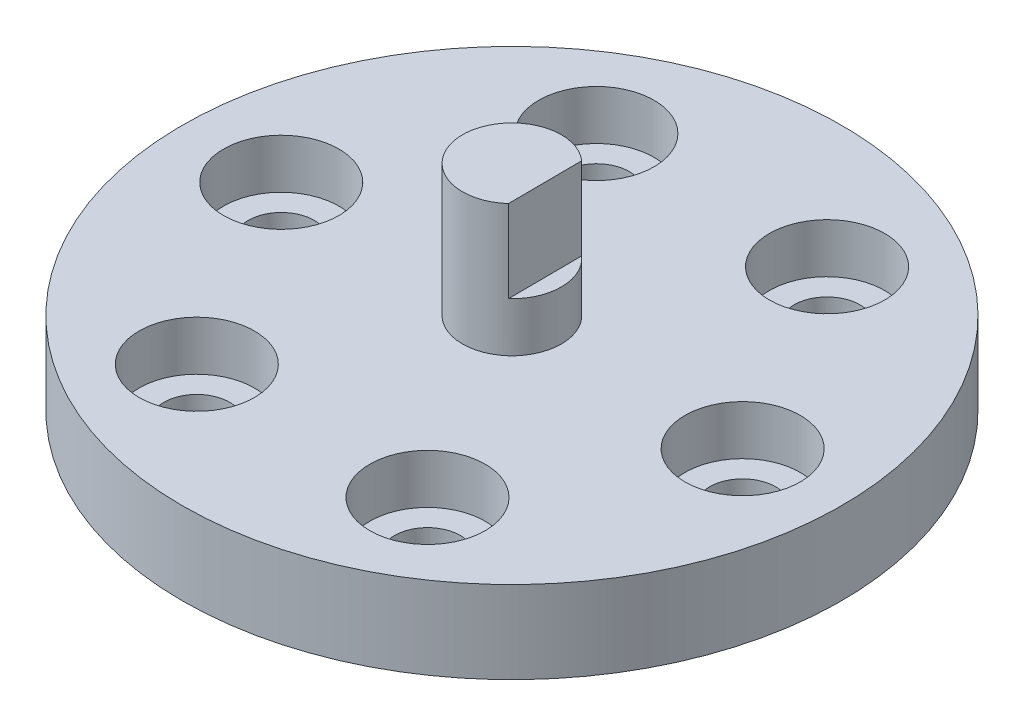
SolidWorks part; units mm, degrees
ref_plane "前视基准面" through (0, 0, 0) normal (0, 0, 1) x (1, 0, 0)
ref_plane "上视基准面" through (0, 0, 0) normal (0, 1, 0) x (1, 0, 0)
ref_plane "右视基准面" through (0, 0, 0) normal (1, 0, 0) x (0, 0, -1)
other "Configuration Table"
sketch "草图1" plane through (0, 0, 0) normal (0, 1, 0) x (1, 0, 0)
  circle A0 centre (0, 0) radius 20
  dimension "D1" = 40
extrude "凸台-拉伸1" add sketch "草图1" along normal blind 5
sketch "草图2" plane through (0, 5, 0) normal (0, 1, 0) x (1, 0, 0)
  circle A0 centre (14, 0) radius 2
  circle A1 centre (7, -12.1244) radius 2
  circle A2 centre (-7, -12.1244) radius 2
  circle A3 centre (-14, 0) radius 2
  circle A4 centre (-7, 12.1244) radius 2
  circle A5 centre (7, 12.1244) radius 2
  point P16 (0, 0)
  dimension "D1" = 4
  dimension "D2" = 14
  dimension "D3" = 6
extrude "切除-拉伸1" cut sketch "草图2" against normal through all
sketch "草图3" plane through (0, 5, 0) normal (0, 1, 0) x (1, 0, 0)
  circle A0 centre (14, 0) radius 3.5
  circle A1 centre (7, -12.1244) radius 3.5
  circle A2 centre (-7, -12.1244) radius 3.5
  circle A3 centre (-14, 0) radius 3.5
  circle A4 centre (-7, 12.1244) radius 3.5
  circle A5 centre (7, 12.1244) radius 3.5
  point P15 (0, 0)
  dimension "D1" = 7
  dimension "D2" = 6
extrude "切除-拉伸2" cut sketch "草图3" against normal blind 3
sketch "草图4" plane through (0, 5, 0) normal (0, 1, 0) x (1, 0, 0)
  circle A0 centre (0, 0) radius 3
  dimension "D1" = 6
extrude "凸台-拉伸2" add sketch "草图4" along normal blind 8
sketch "草图5" plane through (0, 13, 0) normal (0, 1, 0) x (1, 0, 0)
  line L0 (2.0145, -2.223) -> (1.9854, 2.2491)
  circle A0 centre (0, 0) radius 3 construction
  arc A1 (2.0145, -2.223) -> (1.9854, 2.2491) centre (0, 0) ccw
  dimension "D1" = 2
extrude "切除-拉伸3" cut sketch "草图5" against normal blind 5
